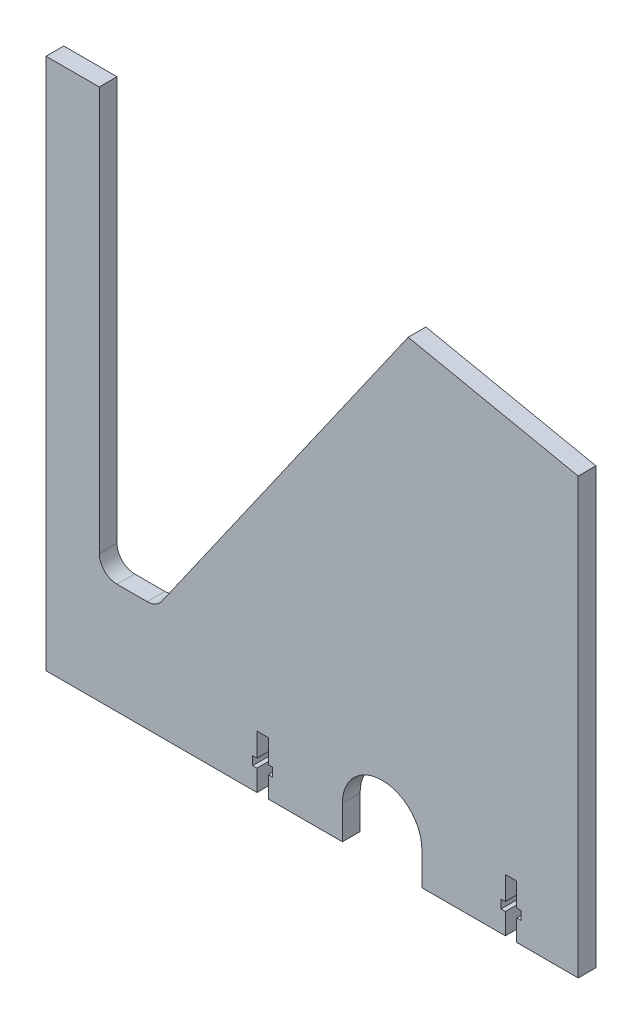
SolidWorks part; units mm, degrees
material "Balsa"
ref_plane "Plan de face" through (0, 0, 0) normal (0, 0, 1) x (1, 0, 0)
ref_plane "Plan de dessus" through (0, 0, 0) normal (0, 1, 0) x (1, 0, 0)
ref_plane "Plan de droite" through (0, 0, 0) normal (1, 0, 0) x (0, 0, -1)
sketch "Esquisse1" plane through (0, 0, 0) normal (0, 0, 1) x (1, 0, 0)
  line L0 (-79.8831, 98.9305) -> (-79.8831, -51.0695)
  line L1 (-79.8831, -51.0695) -> (-20.434, -51.0695)
  line L2 (70.1169, -51.0695) -> (70.1169, -43.5695)
  line L4 (-64.8831, -19.9474) -> (-64.8831, 98.9305)
  line L5 (-64.8831, 98.9305) -> (-79.8831, 98.9305)
  line L10 (-64.8831, -19.9474) -> (-48.7588, -19.9474)
  line L11 (-48.7588, -19.9474) -> (22.1947, 81.3848)
  line L12 (70.1169, -43.5695) -> (70.1169, 71.4491)
  line L13 (70.1169, 71.4491) -> (22.1947, 81.3848)
  line L14 (49.566, -51.0695) -> (49.566, -45.1017)
  line L15 (49.566, -36.0695) -> (52.766, -36.0695)
  line L16 (52.766, -36.0695) -> (52.766, -42.6817)
  line L17 (52.766, -51.0695) -> (70.1169, -51.0695)
  line L18 (49.566, -45.1017) -> (48.366, -45.1017)
  line L19 (48.366, -45.1017) -> (48.366, -42.6817)
  line L20 (48.366, -42.6817) -> (49.566, -42.6817)
  line L21 (52.766, -42.6817) -> (53.966, -42.6817)
  line L22 (53.966, -42.6817) -> (53.966, -45.1017)
  line L23 (53.966, -45.1017) -> (52.766, -45.1017)
  line L24 (49.566, -42.6817) -> (49.566, -36.0695)
  line L25 (52.766, -45.1017) -> (52.766, -51.0695)
  line L26 (-17.234, -36.0695) -> (-17.234, -42.6817)
  line L27 (-20.434, -42.6817) -> (-20.434, -36.0695)
  line L28 (-20.434, -36.0695) -> (-17.234, -36.0695)
  line L29 (-21.634, -45.1017) -> (-21.634, -42.6817)
  line L30 (-21.634, -42.6817) -> (-20.434, -42.6817)
  line L31 (-20.434, -51.0695) -> (-20.434, -45.1017)
  line L32 (-20.434, -45.1017) -> (-21.634, -45.1017)
  line L33 (-16.034, -42.6817) -> (-16.034, -45.1017)
  line L34 (-17.234, -42.6817) -> (-16.034, -42.6817)
  line L35 (-17.234, -45.1017) -> (-17.234, -51.0695)
  line L36 (-16.034, -45.1017) -> (-17.234, -45.1017)
  line L37 (-17.234, -51.0695) -> (3.6404, -51.0695)
  line L38 (3.6404, -51.0695) -> (3.6404, -41.6371)
  line L39 (26.036, -51.0695) -> (26.036, -41.6371)
  line L40 (26.036, -51.0695) -> (49.566, -51.0695)
  arc A0 (3.6404, -41.6371) -> (26.036, -41.6371) centre (14.8382, -41.6371) cw
  point P19 (48.366, -43.8917)
  dimension "D1" = 150
  dimension "D2" = 150
  dimension "D3" = 15
  dimension "D4" = 35
  dimension "D5" = 3.2
  dimension "D6" = 7.5
  dimension "D7" = 15
  dimension "D8" = 1.2
  dimension "D9" = 1.2
  dimension "D11" = 2.42
  dimension "D12" = 2.42
  dimension "D10" = 2
extrude "Boss.-Extru.1" add sketch "Esquisse1" along normal blind 5
fillet "Congé1" radius 5 2 edges at (-64.8831, -19.9474, 2.5) (-48.7588, -19.9474, 2.5)
